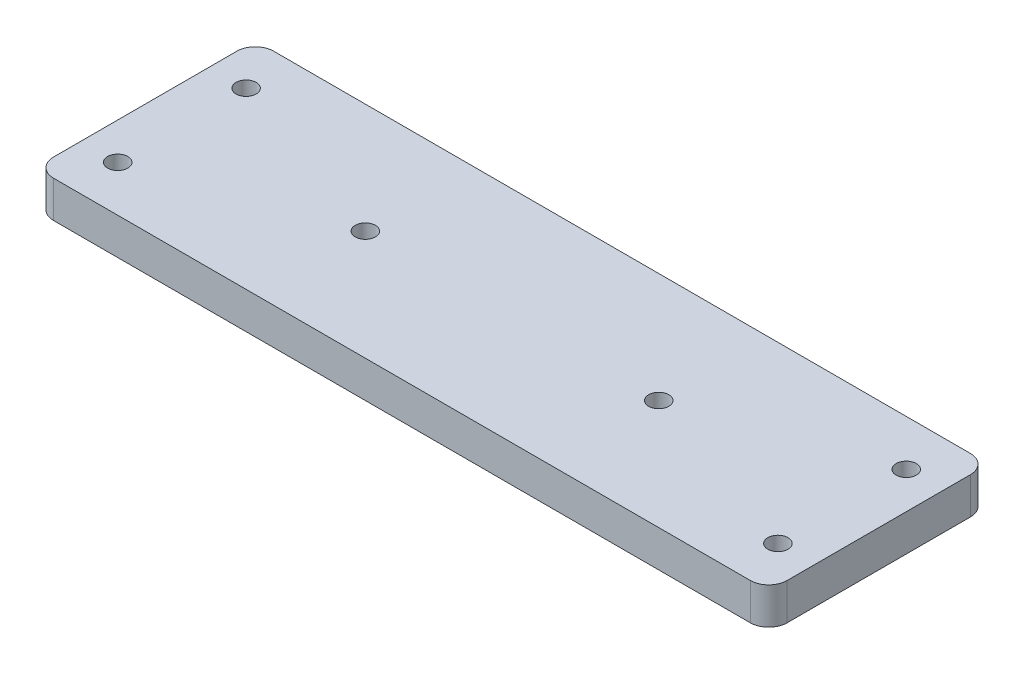
SolidWorks part; units mm, degrees
material "6061-T6 (SS)"
ref_plane "Front Plane" through (0, 0, 0) normal (0, 0, 1) x (1, 0, 0)
ref_plane "Top Plane" through (0, 0, 0) normal (0, 1, 0) x (1, 0, 0)
ref_plane "Right Plane" through (0, 0, 0) normal (1, 0, 0) x (0, 0, -1)
sketch "Sketch1" plane through (0, 0, 0) normal (0, 1, 0) x (1, 0, 0)
  line L0 (-90, 20.25) -> (90, 20.25) construction
  line L1 (-95, -30) -> (95, -30)
  line L2 (-100, -25) -> (-100, 25)
  line L3 (-95, 30) -> (95, 30)
  line L4 (100, -25) -> (100, 25)
  line L5 (-100, -30) -> (100, 30) construction
  line L6 (-100, 30) -> (100, -30) construction
  line L7 (-90, 14.75) -> (90, 14.75) construction
  line L8 (-90, -20.25) -> (90, -20.25) construction
  line L9 (-90, -14.75) -> (90, -14.75) construction
  circle A0 centre (-90, 17.5) radius 2.75
  circle A1 centre (-90, -17.5) radius 2.75
  circle A2 centre (90, 17.5) radius 2.75
  circle A3 centre (90, -17.5) radius 2.75
  arc A4 (-90, 20.25) -> (-90, 14.75) centre (-90, 17.5) ccw construction
  arc A5 (-90, -14.75) -> (-90, -20.25) centre (-90, -17.5) ccw construction
  arc A6 (90, -14.75) -> (90, -20.25) centre (90, -17.5) cw construction
  arc A7 (90, 20.25) -> (90, 14.75) centre (90, 17.5) cw construction
  arc A8 (-100, 25) -> (-95, 30) centre (-95, 25) cw
  arc A9 (100, 25) -> (95, 30) centre (95, 25) ccw
  arc A10 (95, -30) -> (100, -25) centre (95, -25) ccw
  arc A11 (-95, -30) -> (-100, -25) centre (-95, -25) cw
  circle A12 centre (-40, 0) radius 2.75
  circle A13 centre (40, 0) radius 2.75
  point P0 (0, 0)
  dimension "D4" = 17.5
  dimension "D5" = 10
  dimension "D6" = 5.5
  dimension "D7" = 10
  dimension "D8" = 5.5
  dimension "D9" = 10
  dimension "D10" = 5.5
  dimension "D11" = 5.5
  dimension "D12" = 10
  dimension "D13" = 5
  dimension "D14" = 5.5
  dimension "D15" = 5.5
  dimension "D1" = 60
  dimension "D2" = 200
  dimension "D3" = 17.5
extrude "Boss-Extrude1" add sketch "Sketch1" along normal blind 10
